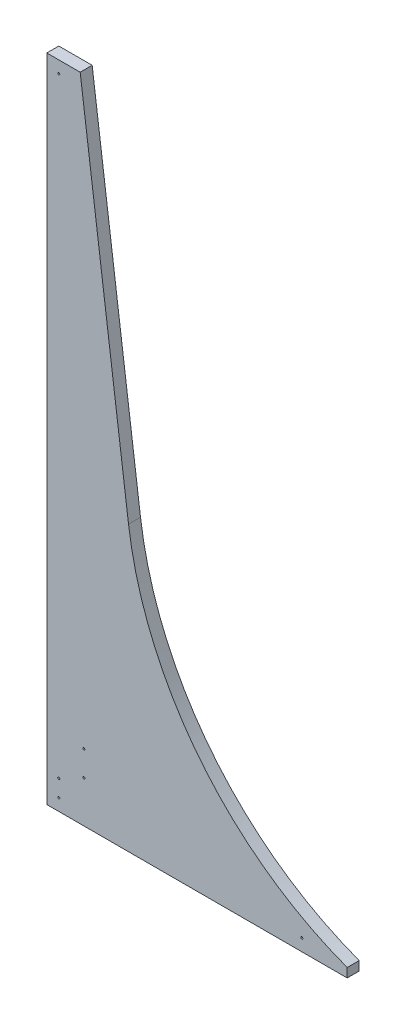
SolidWorks part; units mm, degrees
material "Pine"
ref_plane "Front Plane" through (0, 0, 0) normal (0, 0, 1) x (1, 0, 0)
ref_plane "Top Plane" through (0, 0, 0) normal (0, 1, 0) x (1, 0, 0)
ref_plane "Right Plane" through (0, 0, 0) normal (1, 0, 0) x (0, 0, -1)
sketch "Sketch1" plane through (0, 0, 0) normal (0, 0, 1) x (1, 0, 0)
  line L0 (0, 0) -> (500, 0)
  line L1 (0, 0) -> (0, 990.6)
  line L3 (0, 990.6) -> (50.8, 990.6)
  line L4 (50.8, 990.6) -> (124.3674, 431.8)
  line L7 (457.201, 13.862) -> (457.201, 0)
  circle A1 centre (18.2562, 18.2562) radius 1.5875
  circle A2 centre (388.1438, 18.2562) radius 1.5875
  circle A3 centre (18.2562, 972.3438) radius 1.5875
  circle A4 centre (56.3562, 101.6) radius 1.5875
  circle A6 centre (18.2562, 43.6562) radius 1.5875
  circle A7 centre (56.3562, 63.5) radius 1.5875
  arc A9 (124.3674, 431.8) -> (500, 0) centre (638.1166, 499.4364) ccw
  dimension "D7" = 3.175
  dimension "D8" = 18.2562
  dimension "D10" = 18.2562
  dimension "D11" = 3.175
  dimension "D12" = 18.2562
  dimension "D14" = 3.175
  dimension "D15" = 25.4
  dimension "D16" = 18.2562
  dimension "D17" = 101.6
  dimension "D18" = 50.8
  dimension "D24" = 3.175
  dimension "D1" = 500
  dimension "D2" = 990.6
  dimension "D3" = 42.799
  dimension "D4" = 50.8
  dimension "D5" = 558.8
  dimension "D6" = 97.5
  dimension "D9" = 18.2562
  dimension "D13" = 18.2562
  dimension "D20" = 38.1
  dimension "D21" = 38.1
extrude "Boss-Extrude1" add sketch "Sketch1" along normal blind 18.2562 contours A9 L4 L3 L1 L0 L7 A7 A6 A4 A3 A2 A1
